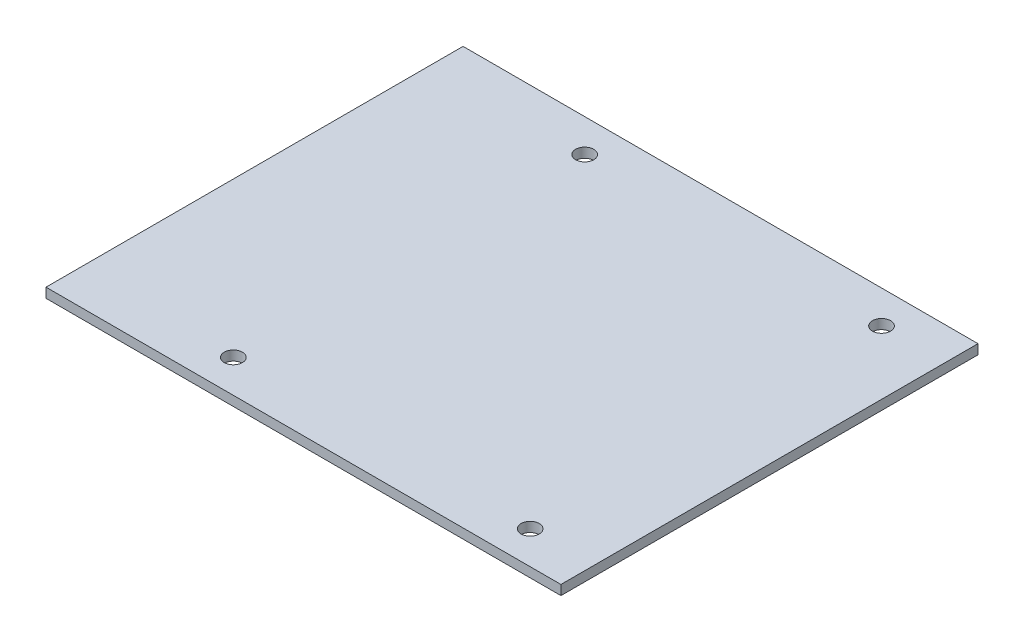
SolidWorks part; units mm, degrees
ref_plane "Alzado" through (0, 0, 0) normal (0, 0, 1) x (1, 0, 0)
ref_plane "Planta" through (0, 0, 0) normal (0, 1, 0) x (1, 0, 0)
ref_plane "Vista lateral" through (0, 0, 0) normal (1, 0, 0) x (0, 0, -1)
sketch "Croquis1" plane through (0, 0, 0) normal (0, 1, 0) x (1, 0, 0)
  line L0 (24.5, 13.4228) -> (24.5, -44.5772) construction
  line L5 (-50, -50) -> (50, 50) construction
  line L6 (-50, 50) -> (50, -50) construction
  line L7 (24.5, -44.5772) -> (-24.5, -44.5772) construction
  line L8 (-50, -50) -> (35, -50)
  line L9 (-24.5, 13.4228) -> (-24.5, -44.5772) construction
  line L10 (-24.5, -15.5772) -> (11.7917, -15.5772) construction
  line L11 (-50, 18.8456) -> (35, 18.8456)
  line L12 (-50, 18.8456) -> (-50, -50)
  line L13 (35, 18.8456) -> (35, -50)
  circle A0 centre (-24.5, 13.4228) radius 1.5
  circle A1 centre (24.5, 13.4228) radius 1.5
  circle A2 centre (-24.5, -44.5772) radius 1.5
  circle A3 centre (24.5, -44.5772) radius 1.5
  point P0 (0, 0)
  dimension "D3" = 3
  dimension "D1" = 85
extrude "Saliente-Extruir1" add sketch "Croquis1" along normal blind 1.6
